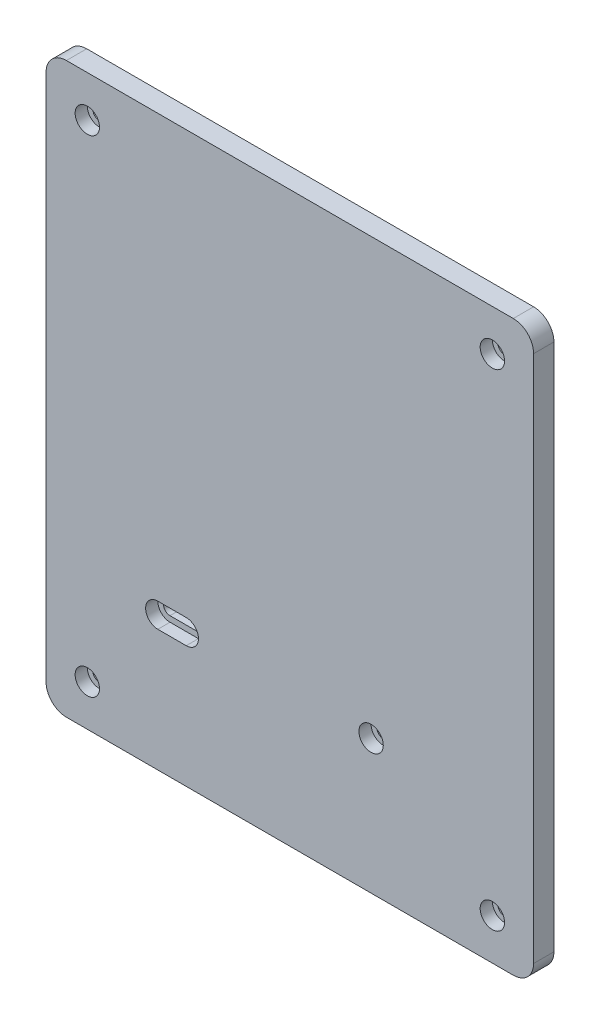
SolidWorks part; units mm, degrees
ref_plane "Alzado" through (0, 0, 0) normal (0, 0, 1) x (1, 0, 0)
ref_plane "Planta" through (0, 0, 0) normal (0, 1, 0) x (1, 0, 0)
ref_plane "Vista lateral" through (0, 0, 0) normal (1, 0, 0) x (0, 0, -1)
sketch "Sketch1" plane through (0, 0, 0) normal (0, 0, 1) x (1, 0, 0)
  line L1 (-60, 70) -> (60, 70)
  line L2 (-60, 70) -> (-60, -70)
  line L3 (-60, -70) -> (60, -70)
  line L4 (60, 70) -> (60, -70)
  line L5 (-60, 70) -> (60, -70) construction
  line L6 (-60, -70) -> (60, 70) construction
  circle A0 centre (-49.85, -59.85) radius 1.65
  circle A1 centre (49.85, -59.85) radius 1.65
  circle A2 centre (49.85, 59.85) radius 1.65
  circle A3 centre (-49.85, 59.85) radius 1.65
  point P0 (0, 0)
  dimension "D3" = 10.15
  dimension "D5" = 3.3
  dimension "D9" = 10.15
  dimension "D10" = 10.15
  dimension "D1" = 120
  dimension "D2" = 140
  dimension "D4" = 10.15
  dimension "D8" = 10.15
  dimension "D6" = 2
  dimension "D7" = 2
extrude "Boss-Extrude1" add sketch "Sketch1" along normal blind 5
fillet "Fillet3" radius 5 4 edges at (-60, 70, 2.5) (-60, -70, 2.5) (60, -70, 2.5) (60, 70, 2.5)
sketch "Sketch3" plane through (0, 0, 5) normal (0, 0, 1) x (1, 0, 0)
  line L0 (-32.5, -37) -> (-25.5, -37) construction
  line L1 (-32.5, -35.4) -> (-25.5, -35.4)
  line L2 (-32.5, -38.6) -> (-25.5, -38.6)
  line L4 (55, 70) -> (-55, 70)
  line L5 (-60, 65) -> (-60, -65)
  line L6 (-55, -70) -> (55, -70)
  line L7 (60, -65) -> (60, 65)
  line L8 (55, 70) -> (-55, 70)
  line L10 (-55, -70) -> (55, -70)
  line L11 (60, -65) -> (60, 65)
  circle A0 centre (20, -37) radius 1.6
  arc A2 (-32.5, -35.4) -> (-32.5, -38.6) centre (-32.5, -37) ccw
  arc A3 (-25.5, -38.6) -> (-25.5, -35.4) centre (-25.5, -37) ccw
  arc A4 (-55, 70) -> (-60, 65) centre (-55, 65) ccw
  arc A5 (-60, -65) -> (-55, -70) centre (-55, -65) ccw
  arc A6 (55, -70) -> (60, -65) centre (55, -65) ccw
  arc A7 (60, 65) -> (55, 70) centre (55, 65) ccw
  arc A8 (-55, 70) -> (-60, 65) centre (-55, 65) ccw
  arc A9 (-60, -65) -> (-55, -70) centre (-55, -65) ccw
  arc A10 (55, -70) -> (60, -65) centre (55, -65) ccw
  arc A11 (60, 65) -> (55, 70) centre (55, 65) ccw
  point P15 (-29, -37)
  dimension "D2" = 40
  dimension "D3" = 3.2
  dimension "D4" = 33
  dimension "D5" = 1.6
  dimension "D6" = 7
  dimension "D7" = 49
  dimension "D1" = 0
extrude "Cut-Extrude3" cut sketch "Sketch3" against normal up to surface (5 mm away) up to face at (0, 0, 0)
sketch "Sketch2" plane through (0, 0, 5) normal (0, 0, 1) x (1, 0, 0)
  line L0 (-32.5, -35.4) -> (-25.5, -35.4) construction
  line L1 (-32.5, -38.6) -> (-25.5, -38.6) construction
  line L2 (-32.5, -35.4) -> (-25.5, -35.4)
  line L3 (-32.5, -38.6) -> (-25.5, -38.6)
  line L4 (-32.5, -37) -> (-25.5, -37) construction
  line L5 (-32.5, -34) -> (-25.5, -34)
  line L6 (-32.5, -40) -> (-25.5, -40)
  circle A0 centre (-49.85, 59.85) radius 3
  circle A1 centre (49.85, 59.85) radius 3
  circle A2 centre (49.85, -59.85) radius 3
  circle A3 centre (-49.85, -59.85) radius 3
  circle A4 centre (49.85, 59.85) radius 1.65 construction
  circle A5 centre (-49.85, -59.85) radius 1.65 construction
  arc A6 (-32.5, -35.4) -> (-32.5, -38.6) centre (-32.5, -37) ccw construction
  arc A7 (-25.5, -38.6) -> (-25.5, -35.4) centre (-25.5, -37) ccw construction
  circle A8 centre (20, -37) radius 1.6 construction
  arc A9 (-32.5, -35.4) -> (-32.5, -38.6) centre (-32.5, -37) ccw
  arc A10 (-25.5, -38.6) -> (-25.5, -35.4) centre (-25.5, -37) ccw
  circle A11 centre (20, -37) radius 1.6
  circle A12 centre (20, -37) radius 3
  arc A13 (-32.5, -34) -> (-32.5, -40) centre (-32.5, -37) ccw
  arc A14 (-25.5, -40) -> (-25.5, -34) centre (-25.5, -37) ccw
  point P21 (-29, -37)
  dimension "D1" = 6
  dimension "D4" = 6
  dimension "D5" = 3
  dimension "D2" = 2
  dimension "D3" = 2
extrude "Cut-Extrude1" cut sketch "Sketch2" against normal blind 3
